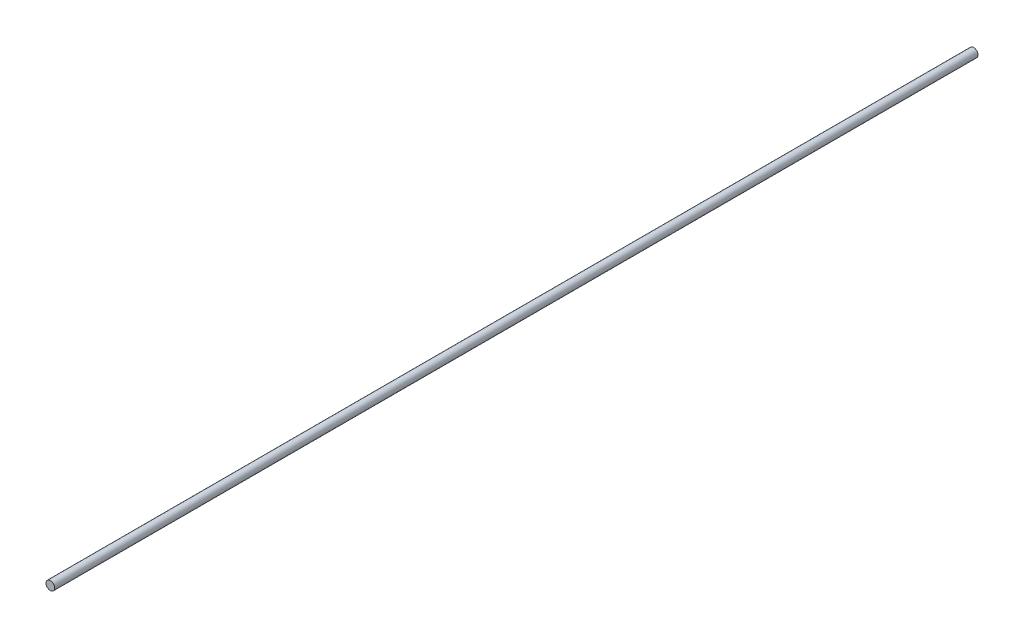
SolidWorks part; units mm, degrees
ref_plane "Plan de face" through (0, 0, 0) normal (0, 0, 1) x (1, 0, 0)
ref_plane "Plan de dessus" through (0, 0, 0) normal (0, 1, 0) x (1, 0, 0)
ref_plane "Plan de droite" through (0, 0, 0) normal (1, 0, 0) x (0, 0, -1)
sketch "Esquisse1" plane through (0, 0, 0) normal (0, 0, 1) x (1, 0, 0)
  circle A0 centre (0, 0) radius 3
  dimension "D1" = 6
extrude "Boss.-Extru.1" add sketch "Esquisse1" along normal blind 640
